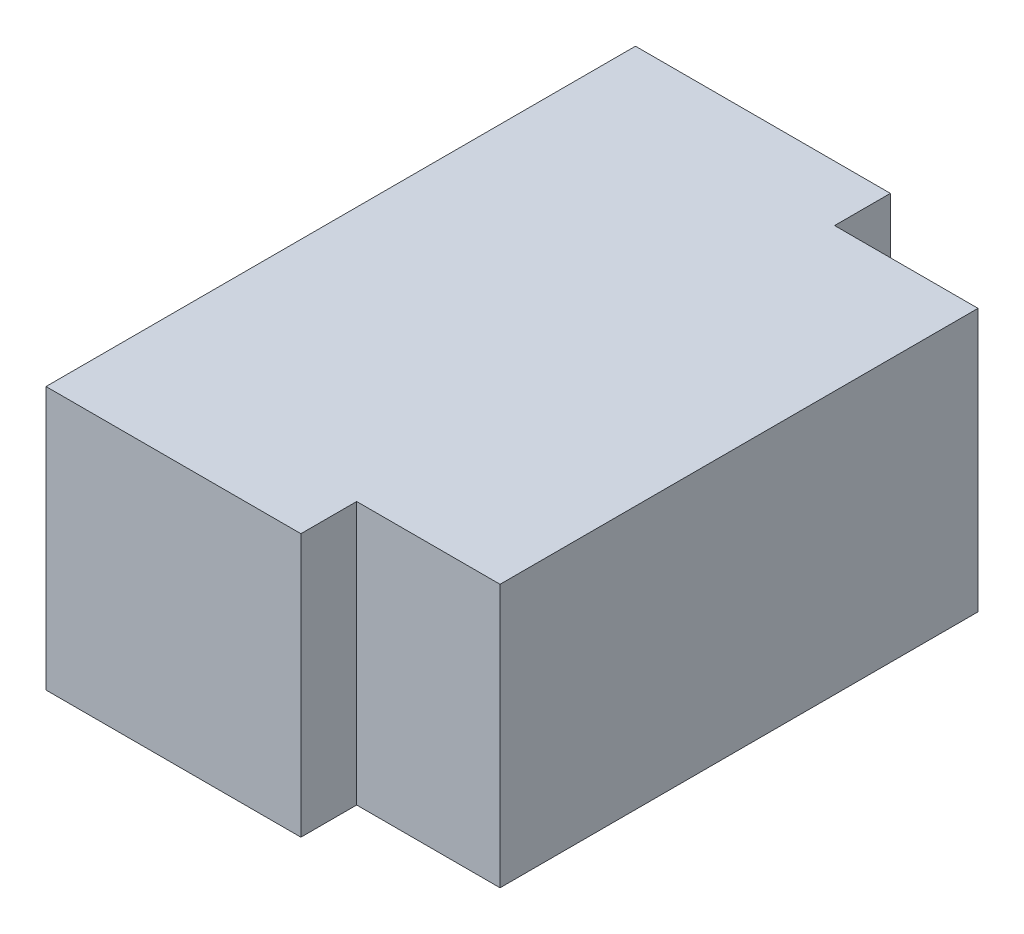
SolidWorks part; units mm, degrees
material "Plastique personnalisé"
ref_plane "Plan de face" through (0, 0, 0) normal (0, 0, 1) x (1, 0, 0)
ref_plane "Plan de dessus" through (0, 0, 0) normal (0, 1, 0) x (1, 0, 0)
ref_plane "Plan de droite" through (0, 0, 0) normal (1, 0, 0) x (0, 0, -1)
sketch "Esquisse1" plane through (0, 0, 0) normal (0, 1, 0) x (1, 0, 0)
  line L1 (8.3882, 24.2506) -> (26.3882, 24.2506)
  line L2 (-23.6118, 24.2506) -> (-23.6118, -35.7494)
  line L3 (8.3882, -35.7494) -> (26.3882, -35.7494)
  line L4 (26.3882, 24.2506) -> (26.3882, -35.7494)
  line L6 (-23.6118, -35.7494) -> (-23.6118, -42.7494)
  line L7 (-23.6118, -42.7494) -> (8.3882, -42.7494)
  line L8 (8.3882, -35.7494) -> (8.3882, -42.7494)
  line L10 (-23.6118, 24.2506) -> (-23.6118, 31.2506)
  line L11 (-23.6118, 31.2506) -> (8.3882, 31.2506)
  line L12 (8.3882, 24.2506) -> (8.3882, 31.2506)
  dimension "D1" = 60
  dimension "D2" = 50
  dimension "D3" = 18
  dimension "D4" = 18
  dimension "D5" = 7
  dimension "D6" = 7
extrude "Boss.-Extru.1" add sketch "Esquisse1" along normal blind 33 contours L11 L12 L1 L4 L3 L8 L7 L6 L2 L10
